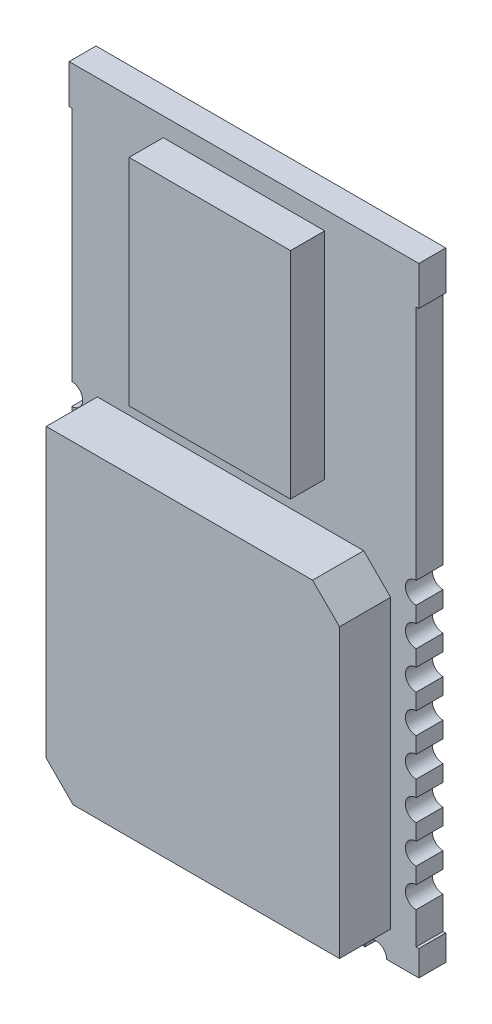
SolidWorks part; units mm, degrees
ref_plane "Front" through (0, 0, 0) normal (0, 0, 1) x (1, 0, 0)
ref_plane "Top" through (0, 0, 0) normal (0, 1, 0) x (1, 0, 0)
ref_plane "Right" through (0, 0, 0) normal (1, 0, 0) x (0, 0, -1)
sketch "草图1" plane through (0, 0, 0) normal (0, 0, 1) x (1, 0, 0)
  line L0 (0, 26.0041) -> (0, -25.4925) construction
  line L1 (-6.5, 11.5) -> (6.5, 11.5)
  line L2 (-6.5, 11.5) -> (-6.5, -11.5)
  line L3 (-6.5, -11.5) -> (6.5, -11.5)
  line L4 (6.5, 11.5) -> (6.5, -11.5)
  line L5 (-25.4615, 0) -> (25.6075, 0) construction
  dimension "D1" = 13
  dimension "D2" = 23
extrude "凸台-拉伸1" add sketch "草图1" against normal blind 1
sketch "草图2" plane through (6.5, 0, 0) normal (1, 0, 0) x (0, 0, -1)
  line L0 (0, 10.05) -> (1, 10.05)
  line L1 (0, -11.5) -> (0, 11.5) construction
  line L2 (1, -11.5) -> (1, 11.5) construction
  line L3 (1, 10.05) -> (1, -10.55)
  line L4 (1, -10.55) -> (0, -10.55)
  line L5 (0, -10.55) -> (0, 10.05)
  line L6 (1, 11.5) -> (0, 11.5) construction
  line L7 (1, -11.5) -> (0, -11.5) construction
  dimension "D1" = 1.45
  dimension "D2" = 0.95
extrude "切除-拉伸1" cut sketch "草图2" against normal blind 0.1
ref_plane "基准面1" through (0, 0, 0) normal (-1, 0, 0) x (0, 0, 1)
mirror "镜向1" about plane through (0, 0, 0) normal (-1, 0, 0) of "切除-拉伸1"
sketch "草图5" plane through (0, 0, 0) normal (0, 0, 1) x (1, 0, 0)
  line L0 (0.3, -11.5) -> (1.1, -11.5)
  line L1 (-6.5, -11.5) -> (6.5, -11.5) construction
  line L2 (0, 0.55) -> (0, -0.55) construction
  arc A0 (1.1, -11.5) -> (0.3, -11.5) centre (0.7, -11.5) ccw
  point P4 (0, -11.5)
  dimension "D1" = 0.8
  dimension "D2" = 0.3
extrude "切除-拉伸3" cut sketch "草图5" against normal up to next
pattern_linear "阵列(线性)8" count 4 spacing 1.4 along (1, 0, 0) of "切除-拉伸3"
mirror "镜向3" about plane through (0, 0, 0) normal (-1, 0, 0) of "阵列(线性)8", "切除-拉伸3"
sketch "草图11" plane through (0, 0, 0) normal (0, 0, 1) x (1, 0, 0)
  line L0 (-6.4, 10.05) -> (-6.4, -10.55) construction
  line L1 (-6.4, -8.55) -> (-6.4, -9.35)
  line L2 (-6.5, -11.5) -> (-5.3, -11.5) construction
  arc A0 (-6.4, -9.35) -> (-6.4, -8.55) centre (-6.4, -8.95) ccw
  dimension "D1" = 0.8
  dimension "D2" = 2.55
extrude "切除-拉伸4" cut sketch "草图11" against normal up to next
pattern_linear "阵列(线性)9" count 8 spacing 1.4 along (0, 1, 0) of "切除-拉伸4"
mirror "镜向4" about plane through (0, 0, 0) normal (-1, 0, 0) of "阵列(线性)9", "切除-拉伸4"
sketch "草图12" plane through (0, 0, 0) normal (0, 0, 1) x (1, 0, 0)
  line L1 (-5.45, 1.23) -> (5.45, 1.23)
  line L2 (-5.45, 1.23) -> (-5.45, -10.45)
  line L3 (-5.45, -10.45) -> (5.45, -10.45)
  line L4 (5.45, 1.23) -> (5.45, -10.45)
  line L5 (0, 20.7814) -> (0, -25.3728) construction
  line L6 (2.5, -11.5) -> (3.1, -11.5) construction
  point P9 (2.8, -11.5)
  dimension "D1" = 10.9
  dimension "D2" = 11.68
  dimension "D3" = 1.05
extrude "凸台-拉伸2" add sketch "草图12" along normal blind 1.9
chamfer "倒角1" distance 1 1 edges at (5.45, 1.23, 0.95)
chamfer "倒角2" distance 1 1 edges at (-5.45, -10.45, 0.95)
ref_plane "基准面2" through (0, 0, -1) normal (0, 0, -1) x (-1, 0, 0)
ref_point "点2"
ref_point "点3"
sketch "草图13" plane through (0, 0, 0) normal (0, 0, 1) x (1, 0, 0)
  line L0 (6.5, 11.5) -> (-6.5, 11.5) construction
  line L1 (-3, 10.8) -> (3, 10.8)
  line L2 (-3, 10.8) -> (-3, 2.8)
  line L3 (-3, 2.8) -> (3, 2.8)
  line L4 (3, 10.8) -> (3, 2.8)
  line L5 (0, 21.1057) -> (0, -19.2921) construction
  dimension "D1" = 6
  dimension "D2" = 8
  dimension "D3" = 0.7
extrude "凸台-拉伸3" add sketch "草图13" along normal blind 1.27 contours L1 L4 L3 L2
ref_plane "基准面3" through (0, 0, 0) normal (-1, 0, 0) x (0, 0, 1)
